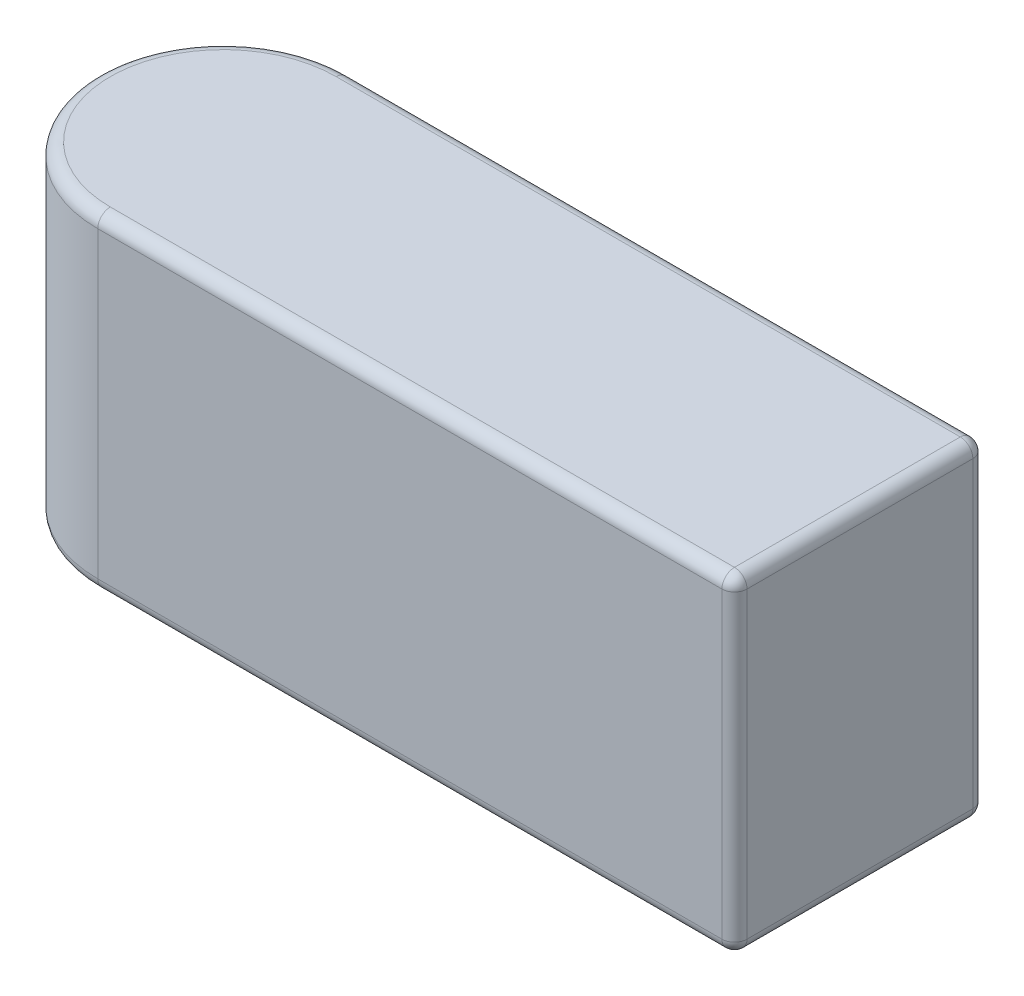
SolidWorks part; units mm, degrees
ref_plane "Front Plane" through (0, 0, 0) normal (0, 0, 1) x (1, 0, 0)
ref_plane "Top Plane" through (0, 0, 0) normal (0, 1, 0) x (1, 0, 0)
ref_plane "Right Plane" through (0, 0, 0) normal (1, 0, 0) x (0, 0, -1)
sketch "Sketch1" plane through (0, 0, 0) normal (0, 0, 1) x (1, 0, 0)
  line L1 (-38.5762, -16.618) -> (38.5763, -16.618)
  line L2 (-38.5762, -16.618) -> (-38.5762, 16.618)
  line L3 (-38.5762, 16.618) -> (38.5763, 16.618)
  line L4 (38.5763, -16.618) -> (38.5763, 16.618)
  line L5 (-38.5762, -16.618) -> (38.5763, 16.618) construction
  line L6 (-38.5762, 16.618) -> (38.5763, -16.618) construction
  point P0 (0, 0)
  dimension "D1" = 33.2359
  dimension "D2" = 77.1525
extrude "Boss-Extrude1" add sketch "Sketch1" along normal blind 25.4
sketch "Sketch2" plane through (0, 16.618, 0) normal (0, 1, 0) x (1, 0, 0)
  line L0 (-25.8762, -12.7) -> (-38.5762, -12.7) construction
  line L1 (38.5763, -25.4) -> (-38.5762, -25.4) construction
  line L3 (-25.8762, 0) -> (-51.2762, 0)
  line L4 (-51.2762, 0) -> (-51.2762, -25.4)
  line L5 (-51.2762, -25.4) -> (-25.8762, -25.4)
  line L6 (-25.8762, 0) -> (-25.8762, -25.4) construction
  line L7 (-38.5762, -25.4) -> (-38.5762, 0) construction
  arc A1 (-25.8762, 0) -> (-38.5762, -12.7) centre (-25.8762, -12.7) ccw
  arc A2 (-25.8762, -25.4) -> (-38.5762, -12.7) centre (-25.8762, -12.7) cw
  dimension "D1" = 25.4
extrude "Cut-Extrude1" cut sketch "Sketch2" against normal through all
fillet "Fillet1" radius 1.27 10 edges at (38.5763, 0, 25.4) (38.5763, 0, 0) (38.5763, -16.618, 12.7) (6.35, -16.618, 0) (-38.5762, -16.618, 12.7) (6.35, -16.618, 25.4) (38.5763, 16.618, 12.7) (6.35, 16.618, 25.4) (-38.5762, 16.618, 12.7) (6.35, 16.618, 0)
